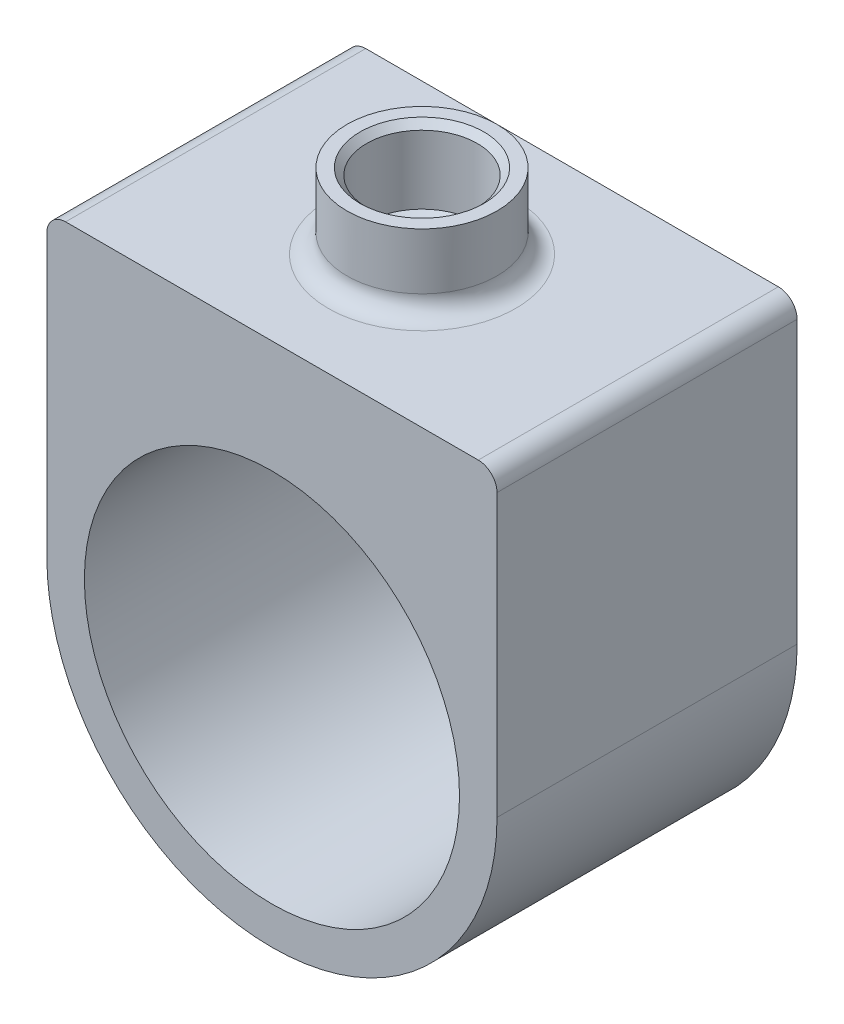
SolidWorks part; units mm, degrees
ref_plane "Front Plane" through (0, 0, 0) normal (0, 0, 1) x (1, 0, 0)
ref_plane "Top Plane" through (0, 0, 0) normal (0, 1, 0) x (1, 0, 0)
ref_plane "Right Plane" through (0, 0, 0) normal (1, 0, 0) x (0, 0, -1)
sketch "Sketch1" plane through (0, 0, 0) normal (0, 0, 1) x (1, 0, 0)
  line L0 (-60, 0) -> (-60, 80)
  line L1 (-60, 80) -> (60, 80)
  line L2 (60, 80) -> (60, 0)
  circle A0 centre (0, 0) radius 50
  arc A1 (-60, 0) -> (60, 0) centre (0, 0) ccw
  point P7 (0, 0)
  point P8 (0, 0)
  dimension "D1" = 100
  dimension "D2" = 10
  dimension "D3" = 80
extrude "Boss-Extrude1" add sketch "Sketch1" along normal mid plane 80
fillet "Fillet1" radius 5 2 edges at (60, 80, 0) (-60, 80, 0)
sketch "Sketch2" plane through (0, 80, 0) normal (0, 1, 0) x (1, 0, 0)
  circle A0 centre (0, 0) radius 20
  dimension "D1" = 40
extrude "Boss-Extrude2" add sketch "Sketch2" along normal blind 20
hole_wizard "M33 Tapped Hole1" positions "3DSketch1" profile "Sketch3" tap size "M33" standard "ISO"
sketch3d "3DSketch1"
  line L0 (0, 100, 0) -> (0, 80, 0) construction
  point P0 (0, 100, 0)
sketch "Sketch3" plane through (0, 100, 0) normal (1, 0, 0) x (0, 0, 1)
  line L0 (0, 0) -> (0, 28.8627)
  line L1 (0, 28.8627) -> (14.75, 20)
  line L2 (14.75, 20) -> (14.75, 1.775)
  line L3 (14.75, 1.775) -> (16.525, 0)
  line L5 (16.525, 0) -> (0, 0)
  line L6 (-14.75, 1.775) -> (-16.525, 0) construction
  line L10 (0, 28.8627) -> (-14.75, 20) construction
  line L11 (0, -6.35) -> (0, 107.95) construction
  dimension "Tap Drill Dia." = 29.5
  dimension "Tap Drill Depth" = 20
  dimension "Near C'Sink Dia." = 33.05
  dimension "Near C'Sink Angle" = 90
  dimension "Drill Angle" = 118
cosmetic thread "Hole Thread1" parameters "D1"=20, "D2"=33
fillet "Fillet2" radius 5 1 edges at (0, 80, -20)
